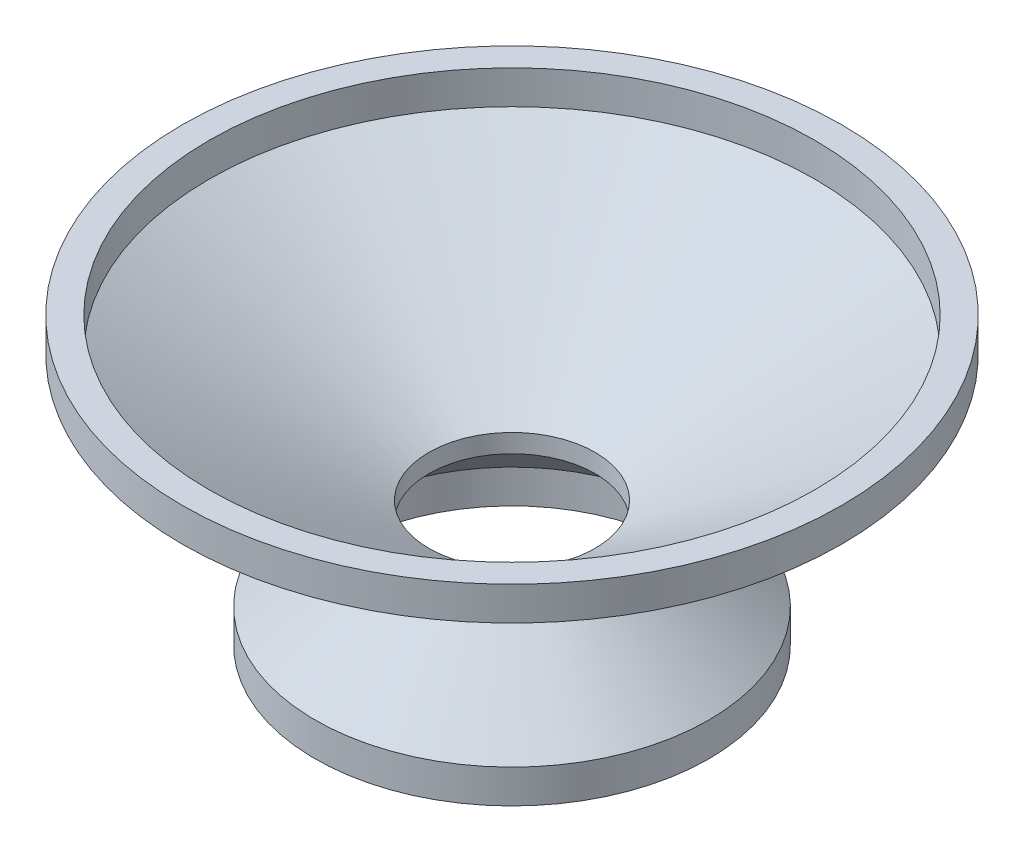
SolidWorks part; units mm, degrees
ref_plane "Front Plane" through (0, 0, 0) normal (0, 0, 1) x (1, 0, 0)
ref_plane "Top Plane" through (0, 0, 0) normal (0, 1, 0) x (1, 0, 0)
ref_plane "Right Plane" through (0, 0, 0) normal (1, 0, 0) x (0, 0, -1)
sketch "Sketch1" plane through (0, 0, 0) normal (0, 0, 1) x (1, 0, 0)
  line L0 (-42.6436, 0) -> (43.9692, 0) construction
  line L1 (0.6628, 0) -> (-13.1936, 8)
  line L2 (0.6628, 0) -> (-5.296, -5)
  line L3 (1.4628, -0.6341) -> (-3.7403, -5)
  line L5 (-13.1936, 8) -> (-11.5936, 8)
  line L6 (-5.296, -5) -> (-3.7403, -5)
  line L7 (6.4064, 7.609) -> (6.4064, -7.609) construction
  line L8 (2.3996, 0.152) -> (-18.835, 12.4117) construction
  line L9 (0.6628, 0) -> (-19.335, 11.5457) construction
  line L10 (0.6628, 0) -> (-15.8334, -13.842) construction
  line L11 (2.3996, 0.152) -> (-15.1906, -14.608) construction
  line L12 (0.6628, 0) -> (2.2628, 0) construction
  line L13 (1.4628, -0.6341) -> (1.4628, 0.4619)
  line L14 (1.4628, 0.4619) -> (-11.5936, 8)
  point P11 (1.4628, 0)
  dimension "D1" = 30
  dimension "D2" = 40
  dimension "D4" = 8
  dimension "D5" = 5
  dimension "D6" = 18
  dimension "D7" = 1.6
  dimension "D8" = 0.8
  dimension "D3" = 1
revolve "Revolve1" add sketch "Sketch1" angle 360 about L7
scale "Scale1" [suppressed]
fillet "Fillet2" radius 0.4 1 edges at (0.6628, 0, 0)
sketch "Sketch2" plane through (0, 8, 0) normal (0, 1, 0) x (1, 0, 0)
  circle A0 centre (6.4064, 0) radius 19.6 construction
  circle A1 centre (6.4064, 0) radius 18 construction
  circle A2 centre (6.4064, 0) radius 19.6
  circle A3 centre (6.4064, 0) radius 18
extrude "Boss-Extrude1" add sketch "Sketch2" along normal blind 2
sketch "Sketch3" plane through (0, -5, 0) normal (0, -1, 0) x (1, 0, 0)
  circle A0 centre (6.4064, 0) radius 10.1466 construction
  circle A1 centre (6.4064, 0) radius 11.7024 construction
  circle A2 centre (6.4064, 0) radius 10.1466
  circle A3 centre (6.4064, 0) radius 11.7024
extrude "Boss-Extrude2" add sketch "Sketch3" along normal blind 2
